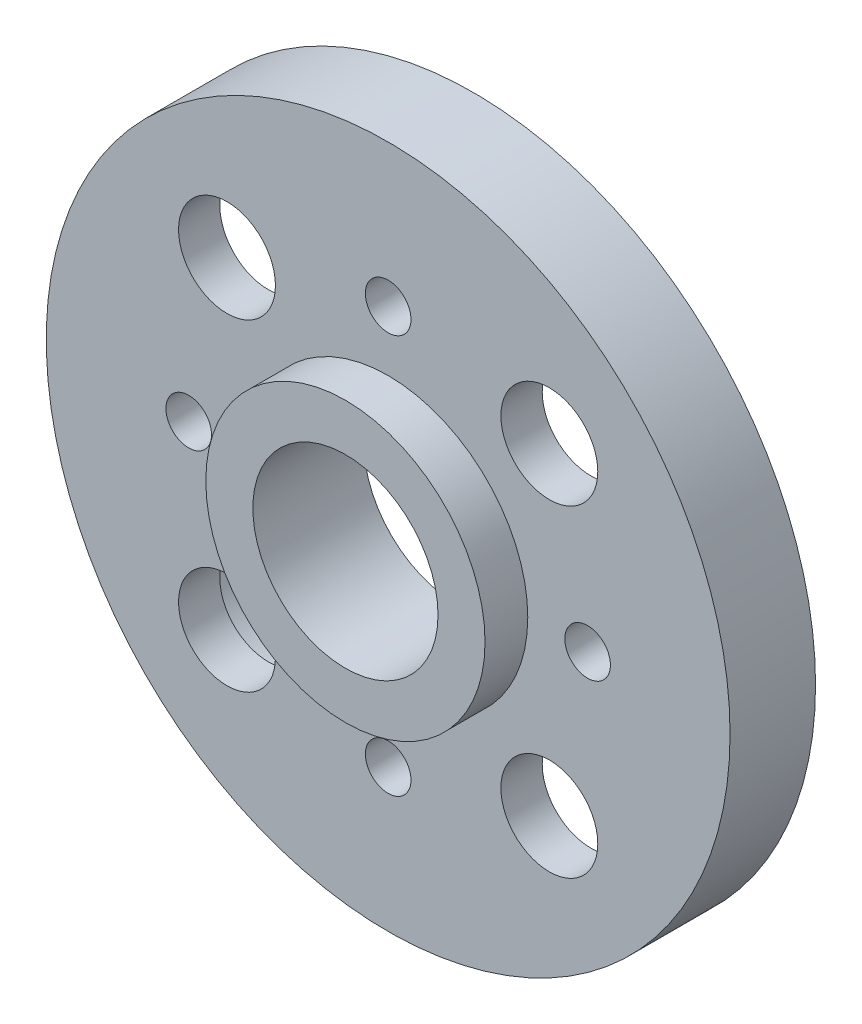
SolidWorks part; units mm, degrees
ref_plane "前视基准面" through (0, 0, 0) normal (0, 0, 1) x (1, 0, 0)
ref_plane "上视基准面" through (0, 0, 0) normal (0, 1, 0) x (1, 0, 0)
ref_plane "右视基准面" through (0, 0, 0) normal (1, 0, 0) x (0, 0, -1)
other "Configuration Table"
sketch "转接板_D24_工具通孔D6.5_截面" plane through (0, 0, 0) normal (0, 0, 1) x (1, 0, 0)
  circle A0 centre (0, 0) radius 12
  circle A1 centre (0, 0) radius 3.25
  dimension "D1" = 24
  dimension "D2" = 6.5
extrude "转接板_D24_厚3_工具通孔D6.5" add sketch "转接板_D24_工具通孔D6.5_截面" along normal blind 3
sketch "轴承内孔定位台_D9.8_高1.5_截面" plane through (0, 0, 0) normal (0, 0, 1) x (1, 0, 0)
  circle A0 centre (0, 0) radius 4.9
  circle A1 centre (0, 0) radius 3.25
  dimension "D1" = 9.8
  dimension "D2" = 6.5
extrude "轴承内孔定位台_D9.8_高1.5" add sketch "轴承内孔定位台_D9.8_高1.5_截面" along normal blind 1.5 from offset 3
sketch "轴承内圈孔位_PCD16_错开45度" plane through (0, 0, 0) normal (0, 0, -1) x (-1, 0, 0)
  point P0 (-5.6569, 5.6569)
  point P1 (5.6569, 5.6569)
  point P2 (5.6569, -5.6569)
  point P3 (-5.6569, -5.6569)
hole_wizard "轴承内圈_4xD3.4通孔_D6.3平底沉孔_PCD16" positions "3D草图1" profile "草图4" counterbore size "M3" standard "ISO" end condition through all
sketch3d "3D草图1"
  point P0 (5.6569, -5.6569, 0)
  point P2 (-5.6569, -5.6569, 0)
  point P4 (-5.6569, 5.6569, 0)
  point P6 (5.6569, 5.6569, 0)
sketch "草图4" plane through (5.6569, -5.6569, 0) normal (1, 0, 0) x (0, 1, 0)
  line L0 (0, 0) -> (0, 4.5)
  line L1 (0, 4.5) -> (1.7, 4.5)
  line L3 (1.7, 4.5) -> (1.7, 1.55)
  line L4 (1.7, 1.55) -> (3.15, 1.55)
  line L5 (3.15, 1.55) -> (3.15, 0)
  line L7 (3.15, 0) -> (0, 0)
  line L11 (0, -6.35) -> (0, 107.95) construction
  dimension "通孔孔直径" = 3.4
  dimension "通孔孔深度" = 4.5
  dimension "柱形沉头孔直径" = 6.3
  dimension "柱形沉头孔深度" = 1.55
sketch "舵盘止口_截面" plane through (0, 0, 0) normal (0, 0, 1) x (1, 0, 0)
  circle A0 centre (0, 0) radius 10.05
  dimension "D1" = 20.1
extrude "原舵盘定位槽_D20.1_深0.6" cut sketch "舵盘止口_截面" along normal blind 0.6
sketch "原舵盘孔位_PCD14" plane through (0, 0, 0.6) normal (0, 0, -1) x (-1, 0, 0)
  point P0 (-7, 0)
  point P1 (0, 7)
  point P2 (7, 0)
  point P3 (0, -7)
hole_wizard "原舵盘_4xM2x0.4通螺纹_PCD14" positions "3D草图2" profile "草图7" tap size "M2" standard "ISO" end condition through all
sketch3d "3D草图2"
  point P0 (0, -7, 0.6)
  point P2 (-7, 0, 0.6)
  point P4 (0, 7, 0.6)
  point P6 (7, 0, 0.6)
sketch "草图7" plane through (0, -7, 0.6) normal (1, 0, 0) x (0, 1, 0)
  line L0 (0, 0) -> (0, 3.9)
  line L1 (0, 3.9) -> (0.8, 3.9)
  line L2 (0.8, 3.9) -> (0.8, 0)
  line L5 (0.8, 0) -> (0, 0)
  line L11 (0, -6.35) -> (0, 107.95) construction
  dimension "通孔螺纹孔钻头直径" = 1.6
  dimension "通孔螺纹孔钻头深度" = 3.9
cosmetic thread "孔螺纹线1" parameters "D2"=2
cosmetic thread "孔螺纹线2" parameters "D2"=2
cosmetic thread "孔螺纹线3" parameters "D2"=2
cosmetic thread "孔螺纹线4" parameters "D2"=2
